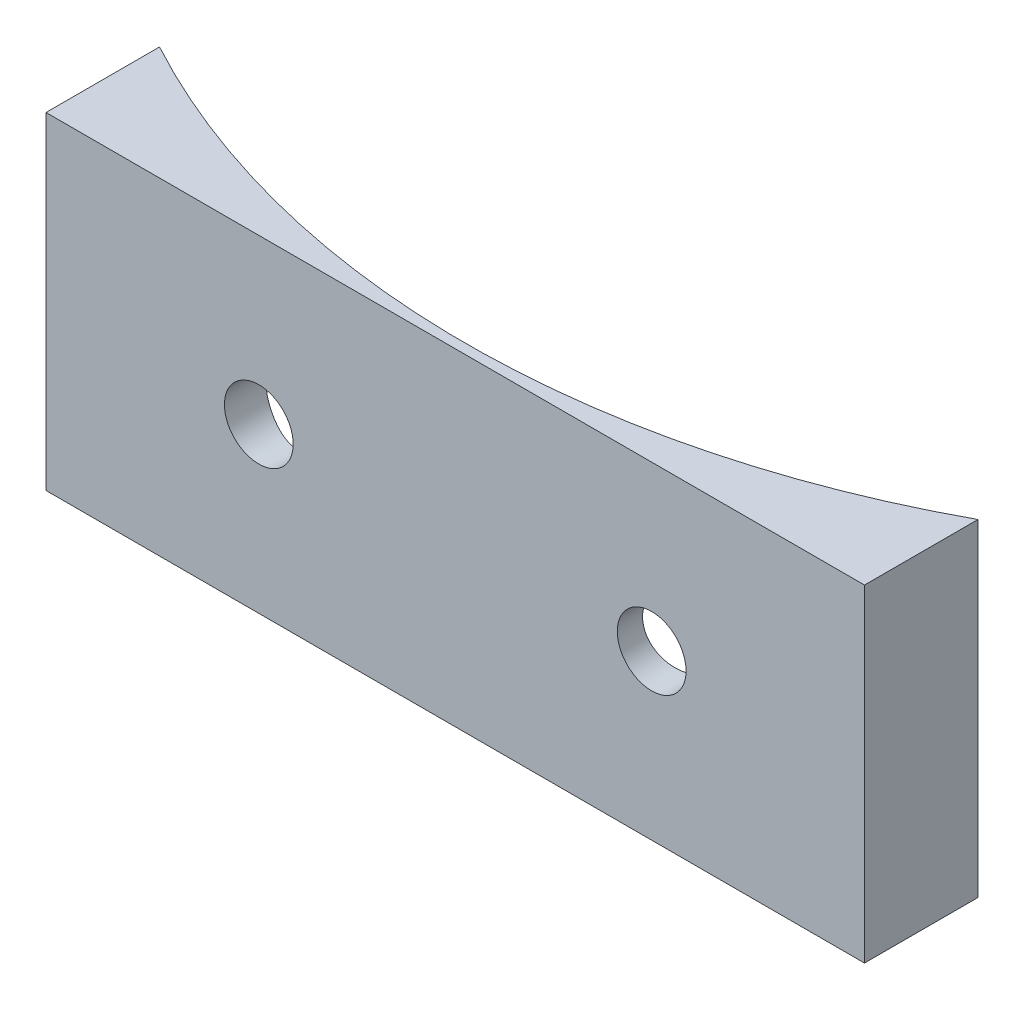
SolidWorks part; units mm, degrees
ref_plane "Спереди" through (0, 0, 0) normal (0, 0, 1) x (1, 0, 0)
ref_plane "Сверху" through (0, 0, 0) normal (0, 1, 0) x (1, 0, 0)
ref_plane "Справа" through (0, 0, 0) normal (1, 0, 0) x (0, 0, -1)
other "Configuration Table"
sketch "Эскиз1" plane through (0, 0, 0) normal (0, 1, 0) x (1, 0, 0)
  line L0 (0, 0) -> (0, -52.5) construction
  line L1 (0, 0) -> (-25, -46.1655) construction
  line L2 (0, 0) -> (25, -46.1655) construction
  line L3 (-25, -46.1655) -> (-25, -53.1)
  line L4 (-25, -53.1) -> (25, -53.1)
  line L5 (25, -53.1) -> (25, -46.1655)
  arc A0 (-25, -46.1655) -> (25, -46.1655) centre (0, 0) ccw
  dimension "D4" = 52.5
  dimension "D1" = 25
  dimension "D2" = 25
  dimension "D3" = 0.6
extrude "Бобышка-Вытянуть1" add sketch "Эскиз1" along normal blind 20
sketch "Эскиз2" plane through (0, 0, 53.1) normal (0, 0, 1) x (1, 0, 0)
  line L0 (0, 0) -> (0, 20) construction
  line L1 (-25, 20) -> (25, 20) construction
  line L2 (1.6, 20) -> (1.6, 0) construction
  line L3 (-25, 0) -> (25, 0) construction
  line L4 (-1.6, 20) -> (-1.6, 0) construction
  line L5 (-25, 20) -> (-25, 0) construction
  circle A0 centre (-12, 10) radius 2.1
  circle A1 centre (12, 10) radius 2.1
  dimension "D3" = 4.2
  dimension "D4" = 13
  dimension "D1" = 1.6
  dimension "D2" = 1.6
extrude "Вырез-Вытянуть1" cut sketch "Эскиз2" against normal blind 20
